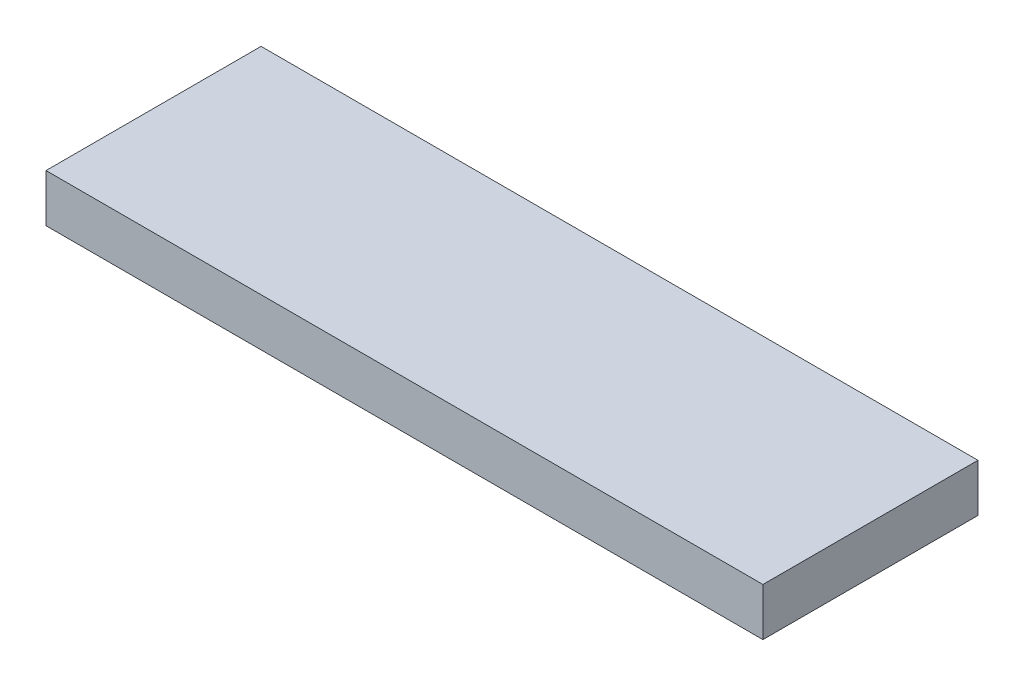
SolidWorks part; units mm, degrees
ref_plane "Front Plane" through (0, 0, 0) normal (0, 0, 1) x (1, 0, 0)
ref_plane "Top Plane" through (0, 0, 0) normal (0, 1, 0) x (1, 0, 0)
ref_plane "Right Plane" through (0, 0, 0) normal (1, 0, 0) x (0, 0, -1)
sketch "Sketch1" plane through (0, 0, 0) normal (0, 1, 0) x (1, 0, 0)
  line L1 (-75, 22.5) -> (75, 22.5)
  line L2 (-75, 22.5) -> (-75, -22.5)
  line L3 (-75, -22.5) -> (75, -22.5)
  line L4 (75, 22.5) -> (75, -22.5)
  line L5 (-75, 22.5) -> (75, -22.5) construction
  line L6 (-75, -22.5) -> (75, 22.5) construction
  point P0 (0, 0)
  dimension "D1" = 45
  dimension "D2" = 150
extrude "Boss-Extrude1" add sketch "Sketch1" along normal blind 10
